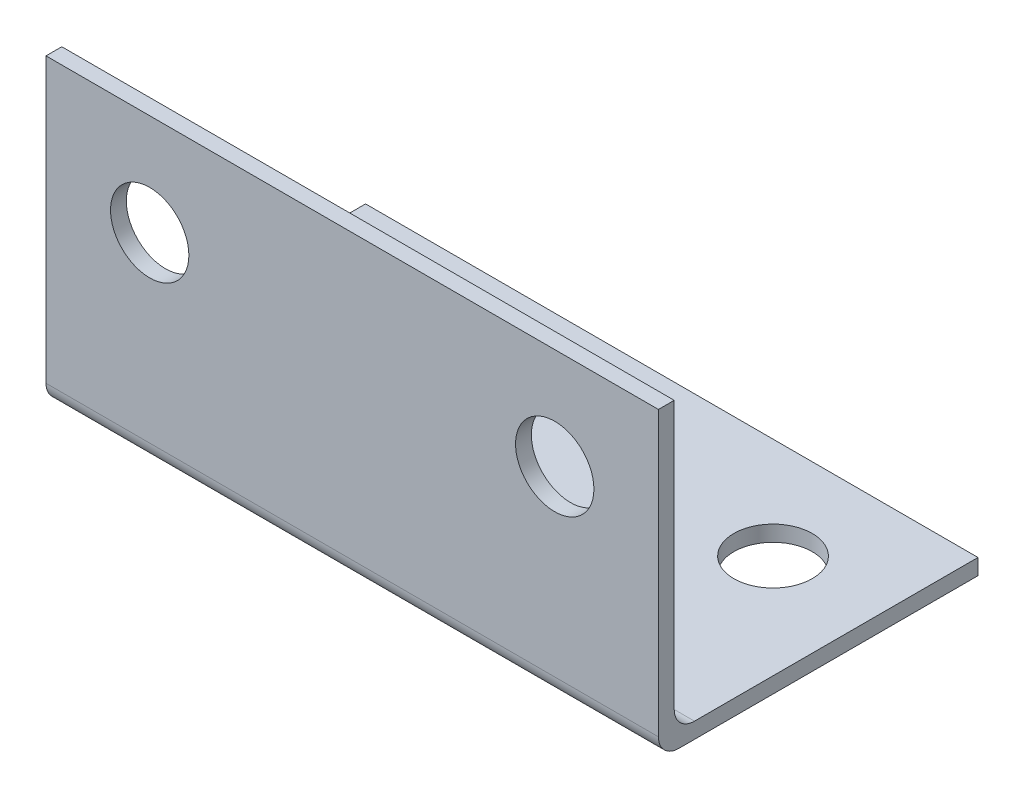
SolidWorks part; units mm, degrees
ref_plane "Front Plane" through (0, 0, 0) normal (0, 0, 1) x (1, 0, 0)
ref_plane "Top Plane" through (0, 0, 0) normal (0, 1, 0) x (1, 0, 0)
ref_plane "Right Plane" through (0, 0, 0) normal (1, 0, 0) x (0, 0, -1)
sketch "Sketch1" plane through (0, 0, 0) normal (0, 0, 1) x (1, 0, 0)
  line L1 (19.2024, -9.525) -> (-19.2024, -9.525)
  line L2 (19.2024, -9.525) -> (19.2024, 9.525)
  line L3 (19.2024, 9.525) -> (-19.2024, 9.525)
  line L4 (-19.2024, -9.525) -> (-19.2024, 9.525)
  line L5 (19.2024, -9.525) -> (-19.2024, 9.525) construction
  line L6 (19.2024, 9.525) -> (-19.2024, -9.525) construction
  point P0 (0, 0)
  dimension "D1" = 38.4048
  dimension "D2" = 19.05
extrude "Boss-Extrude1" add sketch "Sketch1" along normal blind 0.9906
sketch "Sketch2" plane through (0, 0, 0.9906) normal (0, 0, 1) x (1, 0, 0)
  line L0 (0, 9.525) -> (0, -9.525) construction
  line L1 (19.2024, 9.525) -> (-19.2024, 9.525) construction
  line L2 (-19.2024, -9.525) -> (19.2024, -9.525) construction
  circle A0 centre (-12.7, 3.175) radius 1.1879 construction
  circle A1 centre (12.7, 3.175) radius 1.1879 construction
  dimension "D1" = 12.7
  dimension "D2" = 6.35
hole_wizard "#10 (0.1935) Diameter Hole1" positions "Sketch3" profile "Sketch4" hole size "#10" standard "ANSI Inch" end condition through all
sketch "Sketch3" plane through (0, 0, 0.9906) normal (0, 0, 1) x (1, 0, 0)
  point P0 (-12.7, 3.175)
  point P3 (12.7, 3.175)
sketch "Sketch4" plane through (-12.7, 3.175, 0.9906) normal (1, 0, 0) x (0, -1, 0)
  line L0 (0, 0) -> (0, 0.9906)
  line L1 (0, 0.9906) -> (2.4574, 0.9906)
  line L2 (2.4574, 0.9906) -> (2.4574, 0)
  line L5 (2.4574, 0) -> (0, 0)
  line L11 (0, -6.35) -> (0, 107.95) construction
  dimension "Thru Hole Dia." = 4.9149
  dimension "Thru Hole Depth" = 0.9906
sketch "Sketch5" plane through (0, 0, 0) normal (0, 0, -1) x (-1, 0, 0)
  line L0 (-19.2024, -9.525) -> (-19.2024, 9.525) construction
  line L1 (-19.2024, -8.5344) -> (19.2024, -8.5344)
  line L2 (-19.2024, -8.5344) -> (-19.2024, -9.525)
  line L3 (-19.2024, -9.525) -> (19.2024, -9.525)
  line L4 (19.2024, -8.5344) -> (19.2024, -9.525)
  dimension "D1" = 0.9906
extrude "Boss-Extrude2" add sketch "Sketch5" along normal blind 19.05
sketch "Sketch6" plane through (0, -8.5344, 0) normal (0, 1, 0) x (1, 0, 0)
  line L0 (0, 19.05) -> (0, 0) construction
  line L1 (-19.2024, 19.05) -> (19.2024, 19.05) construction
  line L2 (19.2024, 0) -> (-19.2024, 0) construction
  point P7 (-12.7, 12.7)
  point P8 (12.7, 12.7)
  dimension "D1" = 12.7
  dimension "D2" = 6.35
hole_wizard "#10 (0.1935) Diameter Hole2" positions "Sketch7" profile "Sketch8" hole size "#10" standard "ANSI Inch" end condition through all
sketch "Sketch7" plane through (0, -8.5344, 0) normal (0, 1, 0) x (1, 0, 0)
  point P0 (-12.7, 12.7)
  point P3 (12.7, 12.7)
sketch "Sketch8" plane through (-12.7, -8.5344, -12.7) normal (1, 0, 0) x (0, 0, 1)
  line L0 (0, 0) -> (0, 0.9906)
  line L1 (0, 0.9906) -> (2.4574, 0.9906)
  line L2 (2.4574, 0.9906) -> (2.4574, 0)
  line L5 (2.4574, 0) -> (0, 0)
  line L11 (0, -6.35) -> (0, 107.95) construction
  dimension "Thru Hole Dia." = 4.9149
  dimension "Thru Hole Depth" = 0.9906
fillet "Fillet1" radius 1.27 2 edges at (0, -8.5344, 0) (0, -9.525, 0.9906)
